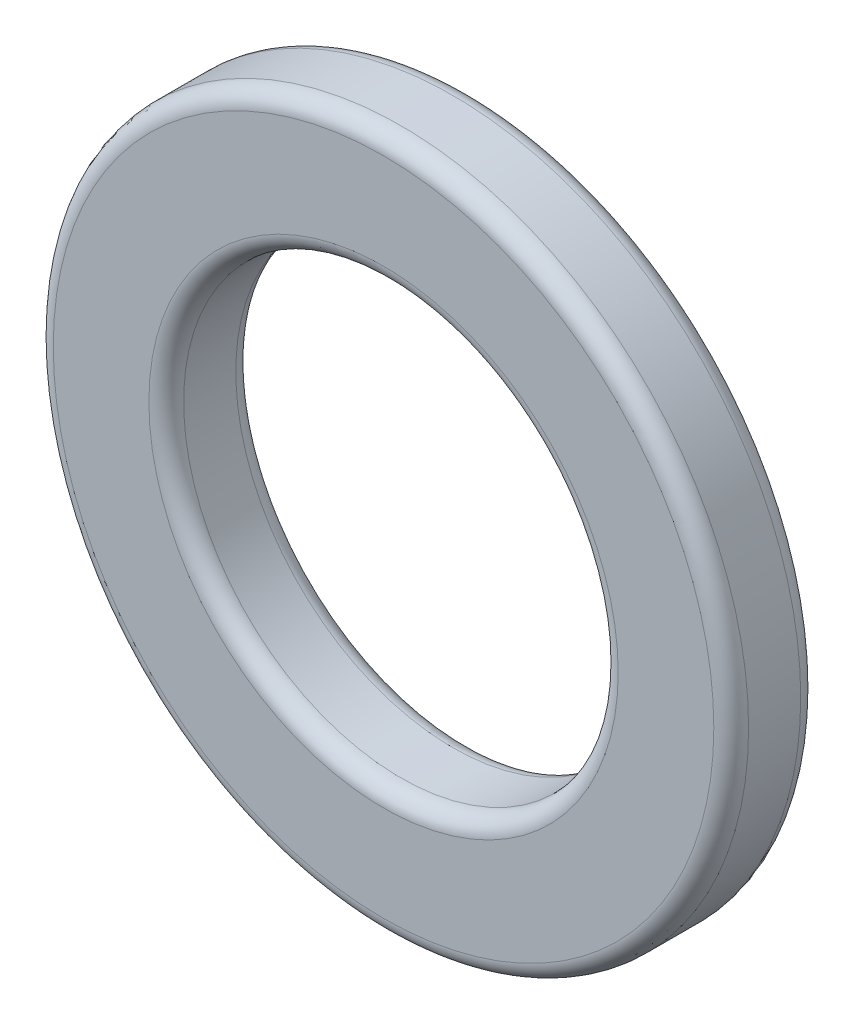
SolidWorks part; units mm, degrees
material "AISI 1020"
ref_plane "Front Plane" through (0, 0, 0) normal (0, 0, 1) x (1, 0, 0)
ref_plane "Top Plane" through (0, 0, 0) normal (0, 1, 0) x (1, 0, 0)
ref_plane "Right Plane" through (0, 0, 0) normal (1, 0, 0) x (0, 0, -1)
sketch "Sketch1" plane through (0, 0, 0) normal (0, 0, 1) x (1, 0, 0)
  circle A0 centre (0, 0) radius 6.35
  circle A1 centre (0, 0) radius 10.16
  dimension "D1" = 12.7
  dimension "D2" = 20.32
extrude "Boss-Extrude1" add sketch "Sketch1" along normal blind 2.54
fillet "Fillet1" radius 0.508 4 edges at (6.35, 0, 2.54) (10.16, 0, 2.54) (10.16, 0, 0) (6.35, 0, 0)
